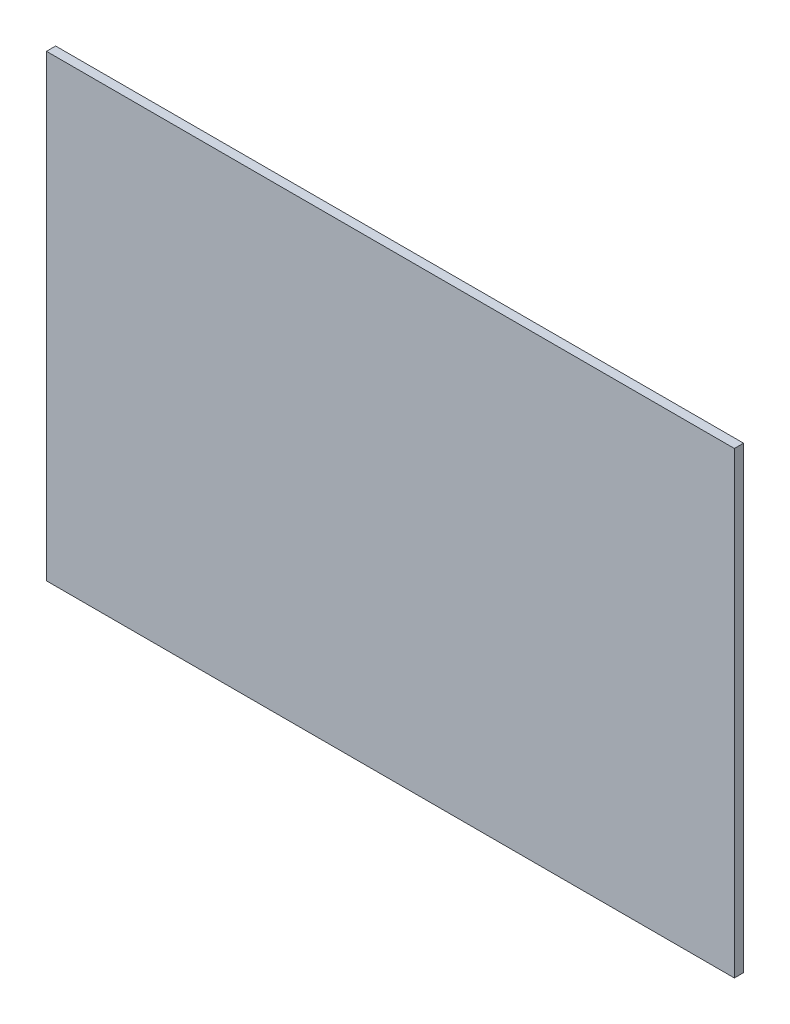
SolidWorks part; units mm, degrees
ref_plane "Front Plane" through (0, 0, 0) normal (0, 0, 1) x (1, 0, 0)
ref_plane "Top Plane" through (0, 0, 0) normal (0, 1, 0) x (1, 0, 0)
ref_plane "Right Plane" through (0, 0, 0) normal (1, 0, 0) x (0, 0, -1)
sketch "Sketch1" plane through (0, 0, 0) normal (0, 0, 1) x (1, 0, 0)
  line L1 (-300, -217.8914) -> (300, -217.8914)
  line L2 (-300, -217.8914) -> (-300, 182.1086)
  line L3 (-300, 182.1086) -> (300, 182.1086)
  line L4 (300, -217.8914) -> (300, 182.1086)
  line L5 (-300, -217.8914) -> (300, 182.1086) construction
  line L6 (-300, 182.1086) -> (300, -217.8914) construction
  point P0 (0, -17.8914)
  point P7 (-709.2652, 414.0575)
  point P8 (-519.4888, 325.8786)
  point P9 (-773.4824, 292.3323)
  dimension "D1" = 600
  dimension "D2" = 400
extrude "Boss-Extrude1" add sketch "Sketch1" along normal blind 8
